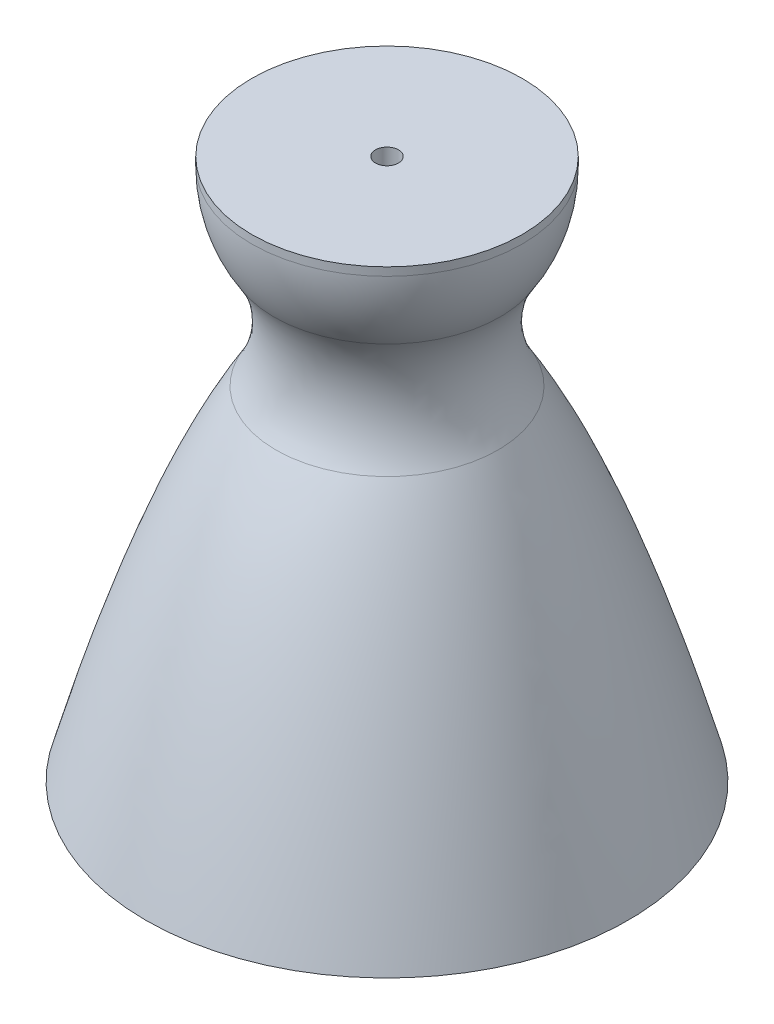
SolidWorks part; units mm, degrees
ref_plane "Front Plane" through (0, 0, 0) normal (0, 0, 1) x (1, 0, 0)
ref_plane "Top Plane" through (0, 0, 0) normal (0, 1, 0) x (1, 0, 0)
ref_plane "Right Plane" through (0, 0, 0) normal (1, 0, 0) x (0, 0, -1)
sketch "Sketch2" plane through (0, 0, 0) normal (1, 0, 0) x (0, 0, -1)
  line L0 (150.8862, 0) -> (0, 0) construction
  line L1 (0, 180) -> (0, 0) construction
  line L2 (-47, 200) -> (-47, 196.9526)
  line L3 (-50, 200) -> (-47, 200)
  line L4 (-50, 200) -> (-50, 196.9526)
  line L5 (-89.1138, 0) -> (-86.0035, 0)
  line L6 (-86.0035, 0) -> (-89.1138, 0) construction
  arc A0 (-41.0575, 126.5391) -> (-41.7554, 169.4483) centre (-75.1596, 147.4448) ccw
  arc A1 (-50, 196.9526) -> (-41.7554, 169.4483) centre (0, 196.9526) ccw
  arc A2 (-47, 196.9526) -> (-39.25, 171.0985) centre (0, 196.9526) ccw
  arc A3 (-38.4999, 124.9711) -> (-39.25, 171.0985) centre (-75.1596, 147.4448) ccw
  arc A4 (-41.0575, 126.5391) -> (-41.7554, 169.4483) centre (-75.1596, 147.4448) ccw construction
  parabola Q1 (-41.0575, 126.5391) -> (-89.1138, 0) focus (0, 146.8308) apex (-0.1545, 159.8278)
  spline S0 degree 1 poles (-38.4999, 124.9711) (-86.2199, -0.7909) knots 0 0 1 1 construction
  spline S1 degree 3 poles (-38.4999, 124.9711) (-39.0045, 124.148) (-39.9898, 122.5099) (-41.9871, 119.0667) (-44.4766, 114.5422) (-47.4693, 108.7313) (-51.4588, 100.4862) (-56.4454, 89.2438) (-62.423, 74.2608) (-68.3914, 57.7882) (-73.3555, 42.8222) (-77.3205, 30.1061) (-80.2903, 20.2) (-82.764, 11.6295) (-84.6471, 4.923) (-85.5823, 1.537) (-86.0756, -0.2631) (-86.1663, -0.5945) (-86.2199, -0.7909) knots 0.502864 0.502864 0.502864 0.502864 0.502971 0.503078 0.503293 0.503508 0.503723 0.504152 0.504582 0.505011 0.505441 0.505656 0.50587 0.506085 0.506193 0.50628 0.506288 0.5063 0.5063 0.5063 0.5063 only from (-38.4999, 124.9711) to (-86.0035, 0)
  point P22 (0, 0)
  point P23 (0, 146.8171)
  point P24 (-75.1596, 146.8308)
  dimension "D5" = 50
  dimension "D6" = 40
  dimension "D1" = 240
  dimension "D4" = 50
  dimension "D3" = 200
  dimension "D7" = 3
revolve "Revolve1" add sketch "Sketch2" angle 360 about L1
sketch "Sketch5" plane through (0, 0, 0) normal (1, 0, 0) x (0, 0, -1)
  line L0 (-38.4999, 124.9711) -> (-47.7456, 109.8892) construction
  line L1 (-33.8611, 130.8544) -> (-3, 161.7155)
  line L2 (0, -1000) -> (0, 49000) construction
  line L3 (-3, 161.7155) -> (0, 161.7155)
  line L4 (0, 161.7155) -> (0, 200)
  line L5 (47, 200) -> (-47, 200) construction
  line L6 (0, 200) -> (-47, 200)
  line L7 (-47, 196.9526) -> (-47, 200)
  arc A0 (-38.4999, 124.9711) -> (-39.25, 171.0985) centre (-75.1596, 147.4448) ccw construction
  arc A1 (-38.4999, 124.9711) -> (-39.25, 171.0985) centre (-75.1596, 147.4448) ccw
  arc A2 (-38.4999, 124.9711) -> (-33.8611, 130.8544) centre (-11.3088, 108.3022) cw
  arc A3 (-47, 196.9526) -> (-39.25, 171.0985) centre (0, 196.9526) ccw construction
  arc A4 (-47, 196.9526) -> (-39.25, 171.0985) centre (0, 196.9526) ccw
  dimension "D1" = 45
  dimension "D2" = 3
revolve "Revolve2" add sketch "Sketch5" angle 360 about L2
sketch "Sketch6" plane through (0, 200, 0) normal (0, 1, 0) x (1, 0, 0)
  circle A0 centre (0, 0) radius 4.25
  dimension "D1" = 8.5
extrude "Cut-Extrude1" cut sketch "Sketch6" against normal through all
